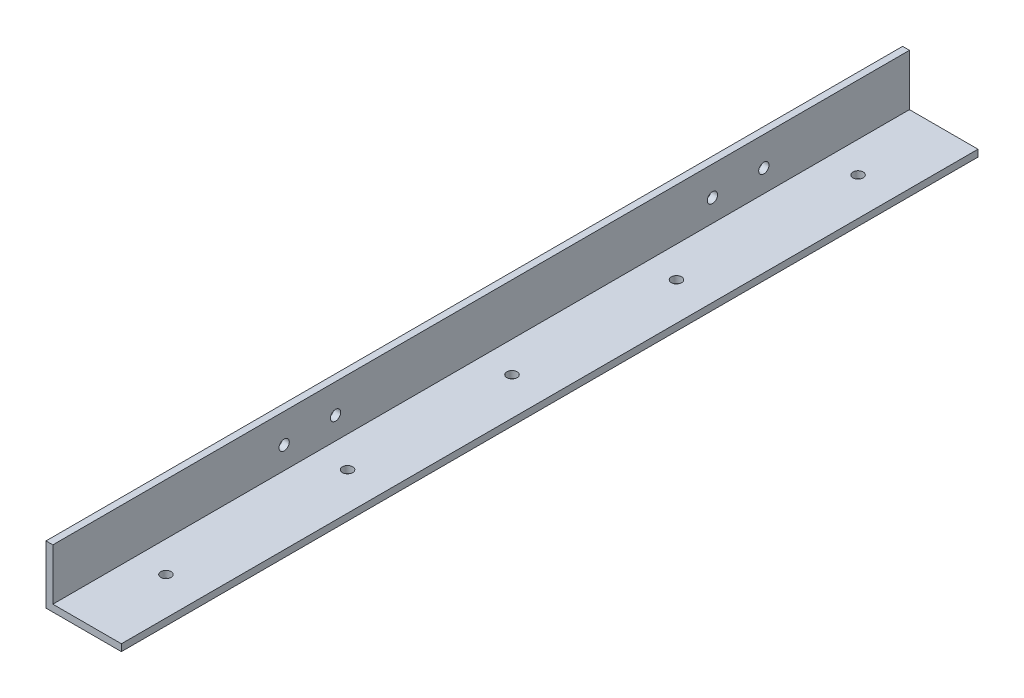
SolidWorks part; units mm, degrees
ref_plane "Front Plane" through (0, 0, 0) normal (0, 0, 1) x (1, 0, 0)
ref_plane "Top Plane" through (0, 0, 0) normal (0, 1, 0) x (1, 0, 0)
ref_plane "Right Plane" through (0, 0, 0) normal (1, 0, 0) x (0, 0, -1)
sketch "Sketch1" plane through (0, 0, 0) normal (0, 0, 1) x (1, 0, 0)
  line L0 (0, 0) -> (0, 17)
  line L1 (0, 17) -> (2, 17)
  line L2 (2, 17) -> (2, 2)
  line L3 (2, 2) -> (22, 2)
  line L4 (22, 2) -> (22, 0)
  line L5 (0, 0) -> (22, 0)
  dimension "D1" = 2
  dimension "D2" = 2
  dimension "D3" = 17
  dimension "D4" = 22
extrude "Boss-Extrude1" add sketch "Sketch1" against normal blind 250
sketch "Sketch2" plane through (0, 2, 0) normal (0, 1, 0) x (1, 0, 0)
  line L0 (11, 250) -> (11, 0) construction
  line L1 (22, 250) -> (2, 250) construction
  line L3 (0, 125) -> (22, 125) construction
  line L4 (0, 250) -> (0, 0) construction
  line L5 (22, 250) -> (22, 0) construction
  line L6 (22, 0) -> (2, 0) construction
  circle A0 centre (11, 226) radius 1.5
  circle A1 centre (11, 24) radius 1.5
  circle A2 centre (11, 125) radius 1.5
  circle A3 centre (11, 173) radius 1.5
  circle A4 centre (11, 77) radius 1.5
  dimension "D1" = 3
  dimension "D2" = 24
  dimension "D3" = 48
  dimension "D4" = 48
  dimension "D5" = 11
extrude "Cut-Extrude1" cut sketch "Sketch2" against normal blind 20
sketch "Sketch3" plane through (0, 0, 0) normal (-1, 0, 0) x (0, 0, 1)
  line L0 (-250, 8.5) -> (0, 8.5) construction
  line L1 (-250, 17) -> (-250, 0) construction
  line L2 (0, 17) -> (0, 0) construction
  line L3 (-125, -38.8376) -> (-125, 76.5538) construction
  line L4 (-250, 0) -> (0, 0) construction
  line L5 (-212.5, 25) -> (-187.5, 25) construction
  line L6 (-212.5, 25) -> (-212.5, 0) construction
  line L7 (-212.5, 0) -> (-187.5, 0) construction
  line L8 (-187.5, 25) -> (-187.5, 0) construction
  line L9 (-212.5, 25) -> (-187.5, 0) construction
  line L10 (-212.5, 0) -> (-187.5, 25) construction
  line L11 (-200, 12.5) -> (-200, 2.484) construction
  line L12 (-87.5, 25) -> (-62.5, 25) construction
  line L13 (-87.5, 25) -> (-87.5, 0) construction
  line L14 (-87.5, 0) -> (-62.5, 0) construction
  line L15 (-62.5, 25) -> (-62.5, 0) construction
  line L16 (-87.5, 25) -> (-62.5, 0) construction
  line L17 (-87.5, 0) -> (-62.5, 25) construction
  line L18 (-75, 12.5) -> (-75, 2.484) construction
  circle A0 centre (-207.5, 8.5) radius 1.5
  circle A1 centre (-192.5, 8.5) radius 1.5
  circle A2 centre (-67.5, 8.5) radius 1.5
  circle A3 centre (-82.5, 8.5) radius 1.5
  point P8 (-125, 8.5)
  point P9 (-200, 12.5)
  point P16 (-75, 12.5)
  dimension "D6" = 3
  dimension "D8" = 3
  dimension "D1" = 25
  dimension "D2" = 25
  dimension "D3" = 75
  dimension "D4" = 50
  dimension "D5" = 5
  dimension "D7" = 5
extrude "Cut-Extrude2" cut sketch "Sketch3" against normal blind 10
